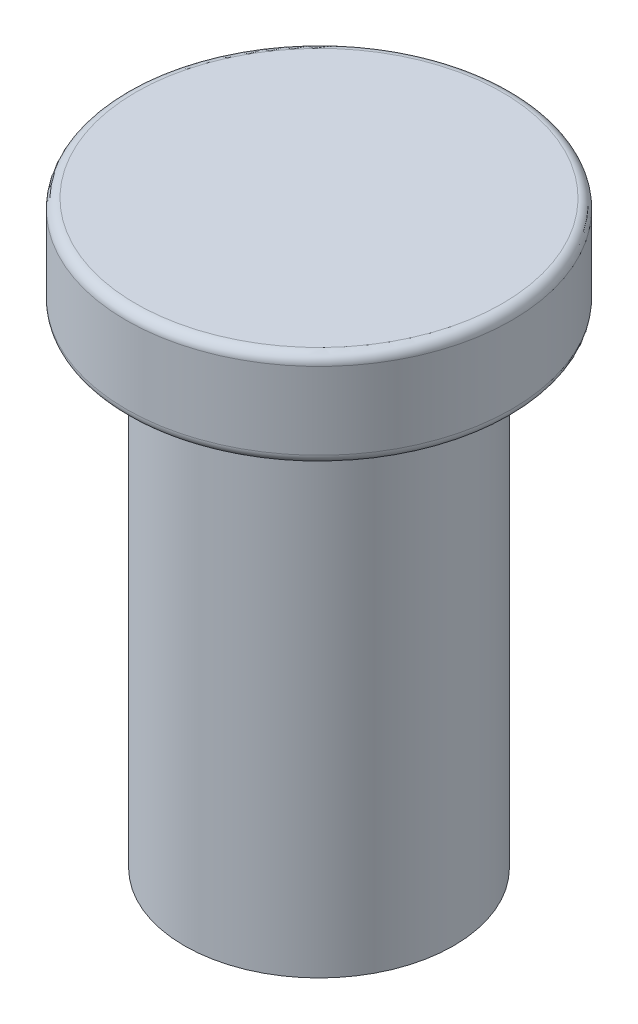
SolidWorks part; units mm, degrees
ref_plane "Plano frontal" through (0, 0, 0) normal (0, 0, 1) x (1, 0, 0)
ref_plane "Plano superior" through (0, 0, 0) normal (0, 1, 0) x (1, 0, 0)
ref_plane "Plano direito" through (0, 0, 0) normal (1, 0, 0) x (0, 0, -1)
sketch "Esboço1" plane through (0, 0, 0) normal (0, 0, 1) x (1, 0, 0)
  line L0 (0, 0) -> (0, 12.07) construction
  line L1 (0, 12.07) -> (-3.81, 12.07)
  line L2 (-4.01, 11.87) -> (-4.01, 10.27)
  line L3 (-3.81, 10.07) -> (-2.8, 10.07)
  line L4 (-2.8, 10.07) -> (-2.8, 0)
  line L5 (-2.8, 0) -> (-2.57, 0)
  line L6 (-2.57, 0) -> (-2.57, 11.02)
  line L7 (-2.37, 11.22) -> (0, 11.22)
  line L8 (0, 12.07) -> (0, 11.22)
  arc A0 (-3.81, 12.07) -> (-4.01, 11.87) centre (-3.81, 11.87) ccw
  arc A1 (-4.01, 10.27) -> (-3.81, 10.07) centre (-3.81, 10.27) ccw
  arc A2 (-2.57, 11.02) -> (-2.37, 11.22) centre (-2.37, 11.02) cw
  dimension "D7" = 0.2
  dimension "D8" = 0.2
  dimension "D1" = 8.02
  dimension "D2" = 5.14
  dimension "D3" = 5.6
  dimension "D4" = 2
  dimension "D5" = 11.22
  dimension "D6" = 12.07
revolve "Revolução1" add sketch "Esboço1" angle 360 about L0
